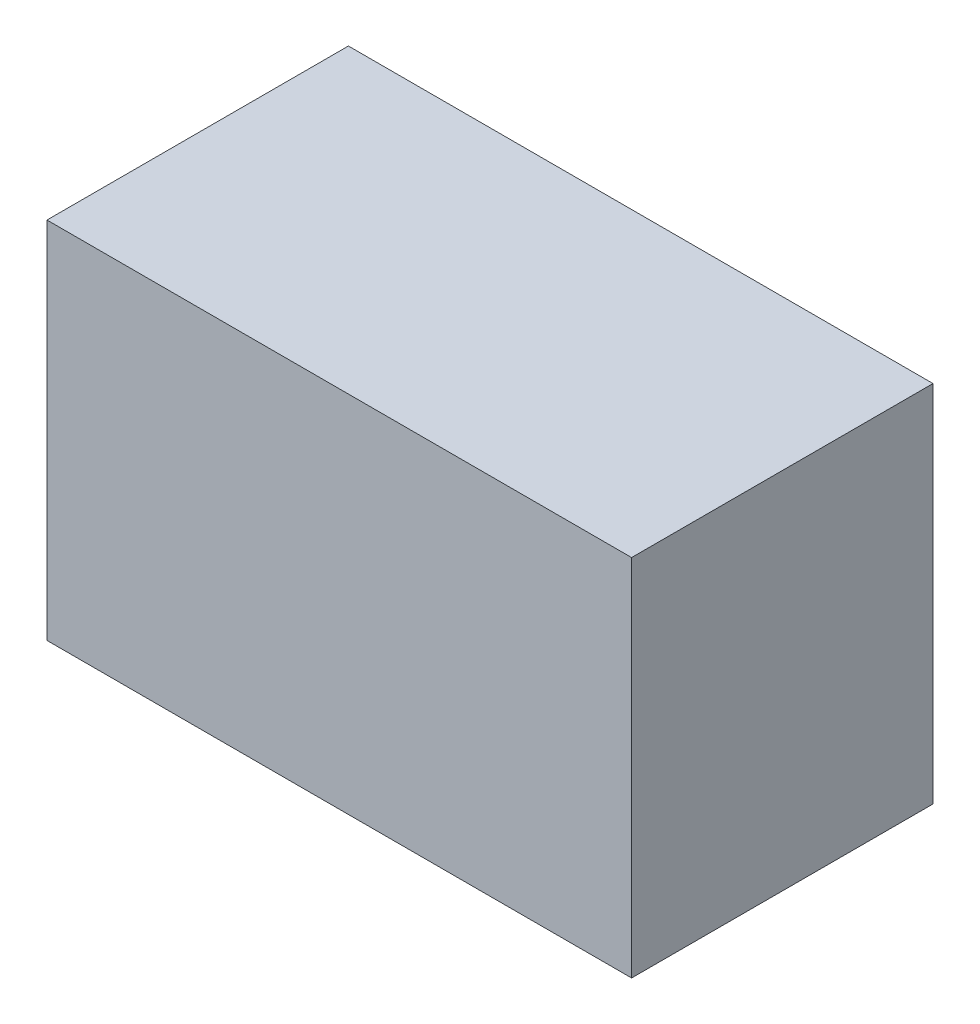
SolidWorks part; units mm, degrees
ref_plane "Front Plane" through (0, 0, 0) normal (0, 0, 1) x (1, 0, 0)
ref_plane "Top Plane" through (0, 0, 0) normal (0, 1, 0) x (1, 0, 0)
ref_plane "Right Plane" through (0, 0, 0) normal (1, 0, 0) x (0, 0, -1)
sketch "Sketch1" plane through (0, 0, 0) normal (0, 0, 1) x (1, 0, 0)
  line L1 (-144.5, -90) -> (144.5, -90)
  line L2 (-144.5, -90) -> (-144.5, 90)
  line L3 (-144.5, 90) -> (144.5, 90)
  line L4 (144.5, -90) -> (144.5, 90)
  line L5 (-144.5, -90) -> (144.5, 90) construction
  line L6 (-144.5, 90) -> (144.5, -90) construction
  point P0 (0, 0)
  dimension "D1" = 289
  dimension "D2" = 180
extrude "Boss-Extrude1" add sketch "Sketch1" along normal blind 149
